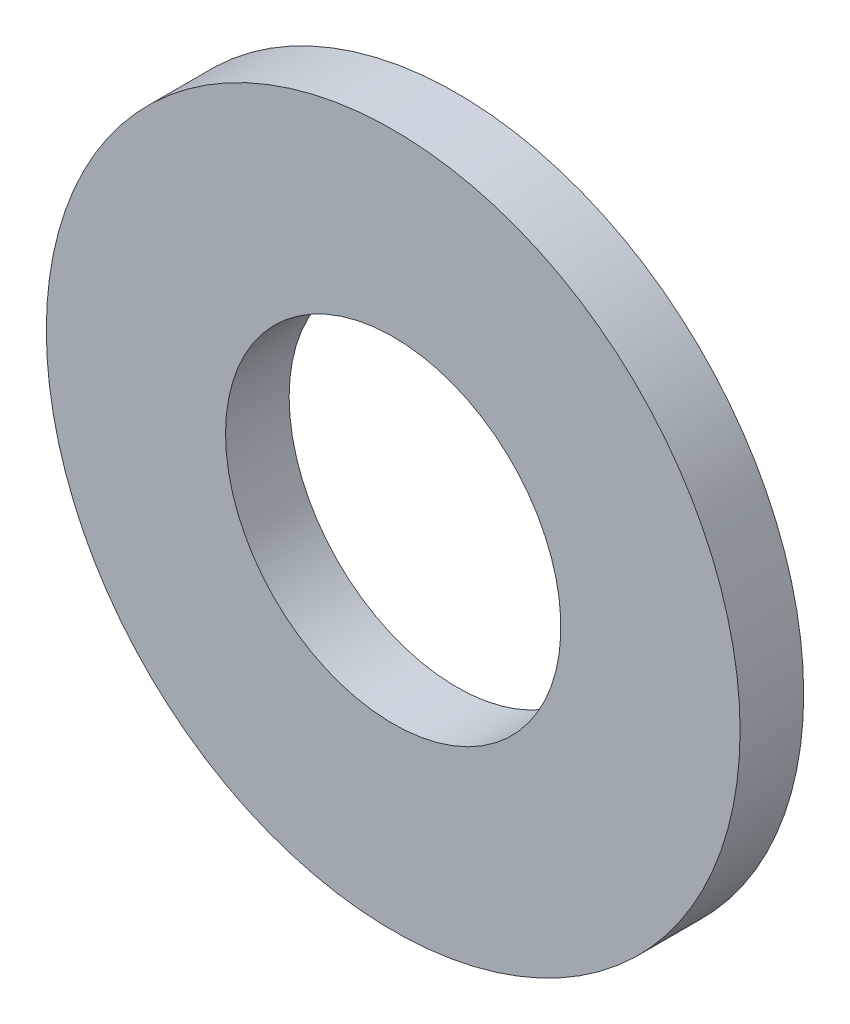
SolidWorks part; units mm, degrees
material "ABS PC"
ref_plane "Front Plane" through (0, 0, 0) normal (0, 0, 1) x (1, 0, 0)
ref_plane "Top Plane" through (0, 0, 0) normal (0, 1, 0) x (1, 0, 0)
ref_plane "Right Plane" through (0, 0, 0) normal (1, 0, 0) x (0, 0, -1)
sketch "Sketch1" plane through (0, 0, 0) normal (0, 0, 1) x (1, 0, 0)
  line L0 (0, 0) -> (0.3753, -1.4006) construction
  line L1 (0, 0) -> (1.45, 0) construction
  circle A0 centre (0, 0) radius 3
  circle A1 centre (0, 0) radius 1.45
  point P5 (0, -3)
  point P9 (0.3753, -1.4006)
  point P11 (0, 3)
  dimension "D1" = 75
  dimension "OD" = 6
  dimension "ID" = 2.9
sketch "Sketch2" plane through (0, 0, 0) normal (1, 0, 0) x (0, 0, -1)
  line L0 (-0.275, 0) -> (0.275, 0) construction
  point P0 (-0.275, 3)
  point P4 (0, 0)
  point P6 (0.275, 3)
  dimension "Thickness" = 0.55
sketch "Sketch3" plane through (0, 0, 0) normal (0, 0, 1) x (1, 0, 0)
  circle A0 centre (0, 0) radius 3 construction
  circle A1 centre (0, 0) radius 1.45 construction
  circle A2 centre (0, 0) radius 3
  circle A3 centre (0, 0) radius 1.45
extrude "Boss-Extrude1" add sketch "Sketch3" along normal up to vertex (0.275 mm away) and the other way up to vertex (0.275 mm away) up to point (0, 3, 0.275) other way up to point (0, 3, -0.275)
